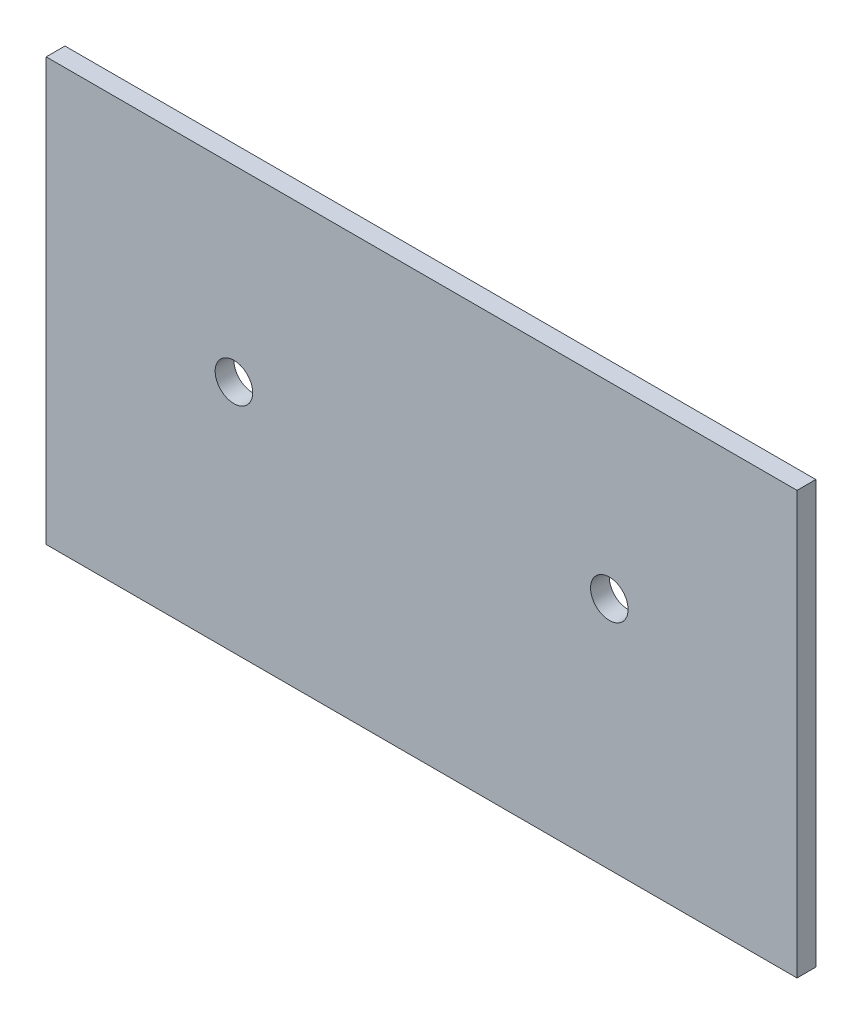
SolidWorks part; units mm, degrees
ref_plane "Front Plane" through (0, 0, 0) normal (0, 0, 1) x (1, 0, 0)
ref_plane "Top Plane" through (0, 0, 0) normal (0, 1, 0) x (1, 0, 0)
ref_plane "Right Plane" through (0, 0, 0) normal (1, 0, 0) x (0, 0, -1)
sketch "Sketch1" plane through (0, 0, 0) normal (0, 0, 1) x (1, 0, 0)
  line L1 (-40, 22.5) -> (40, 22.5)
  line L2 (-40, 22.5) -> (-40, -22.5)
  line L3 (-40, -22.5) -> (40, -22.5)
  line L4 (40, 22.5) -> (40, -22.5)
  line L5 (-40, 22.5) -> (40, -22.5) construction
  line L6 (-40, -22.5) -> (40, 22.5) construction
  point P0 (0, 0)
  dimension "D1" = 45
  dimension "D2" = 80
extrude "Boss-Extrude1" add sketch "Sketch1" along normal blind 2
sketch "Sketch2" plane through (0, 0, 2) normal (0, 0, 1) x (1, 0, 0)
  line L0 (-40, 22.5) -> (-40, -22.5) construction
  line L1 (40, -22.5) -> (40, 22.5) construction
  line L2 (-40, -22.5) -> (40, -22.5) construction
  circle A0 centre (-20, 2.5) radius 2
  circle A1 centre (20, 2.5) radius 2
  dimension "D1" = 4
  dimension "D2" = 4
  dimension "D3" = 20
  dimension "D4" = 20
  dimension "D5" = 25
  dimension "D6" = 25
extrude "Cut-Extrude1" cut sketch "Sketch2" against normal blind 2
